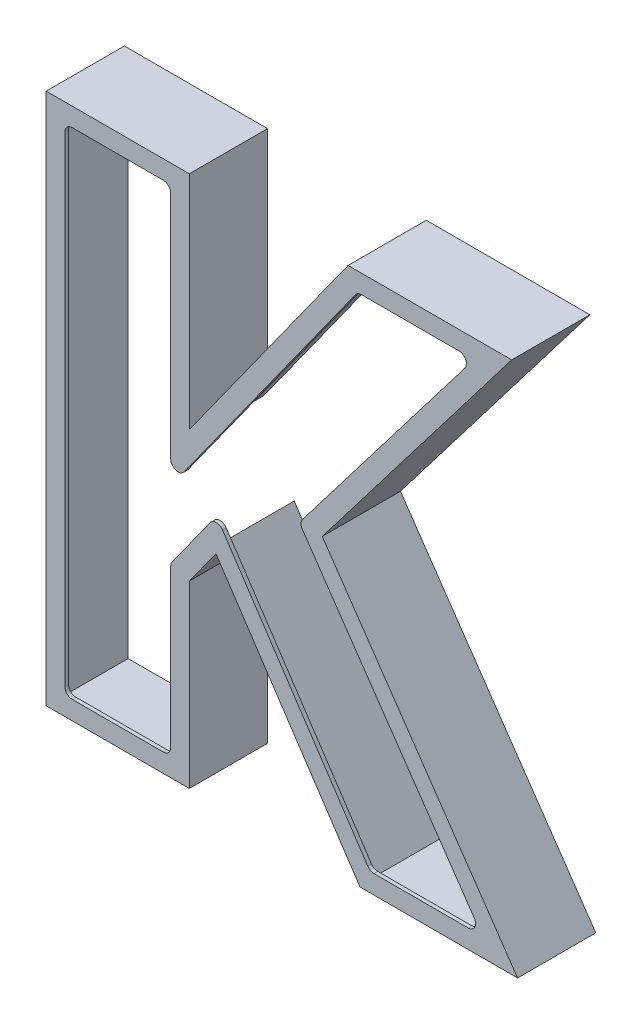
SolidWorks part; units mm, degrees
ref_plane "Front Plane" through (0, 0, 0) normal (0, 0, 1) x (1, 0, 0)
ref_plane "Top Plane" through (0, 0, 0) normal (0, 1, 0) x (1, 0, 0)
ref_plane "Right Plane" through (0, 0, 0) normal (1, 0, 0) x (0, 0, -1)
sketch "Sketch1" plane through (0, 0, 0) normal (0, 0, 1) x (1, 0, 0)
  line L90 (3103.5775, -1502.5826) -> (3065.1345, -1502.5826)
  line L91 (3103.5775, -1562.1032) -> (3103.5775, -1502.5826)
  line L92 (3146.2199, -1502.5826) -> (3103.5775, -1562.1032)
  line L93 (3190.1772, -1502.5826) -> (3146.2199, -1502.5826)
  line L94 (3139.2895, -1569.0911) -> (3190.1772, -1502.5826)
  line L95 (3191.7609, -1645.5826) -> (3139.2895, -1569.0911)
  line L96 (3149.4263, -1645.5826) -> (3191.7609, -1645.5826)
  line L97 (3110.7244, -1587.3803) -> (3149.4263, -1645.5826)
  line L98 (3103.5775, -1597.3267) -> (3110.7244, -1587.3803)
  line L99 (3103.5775, -1645.5826) -> (3103.5775, -1597.3267)
  line L100 (3065.1345, -1502.5826) -> (3065.1345, -1645.5826)
  line L101 (3065.1345, -1645.5826) -> (3103.5775, -1645.5826)
  line L102 (3103.5775, -1502.5826) -> (3065.1345, -1502.5826)
  line L103 (3103.5775, -1562.1032) -> (3103.5775, -1502.5826)
  line L104 (3146.2199, -1502.5826) -> (3103.5775, -1562.1032)
  line L105 (3190.1772, -1502.5826) -> (3146.2199, -1502.5826)
  line L106 (3139.2895, -1569.0911) -> (3190.1772, -1502.5826)
  line L107 (3191.7609, -1645.5826) -> (3139.2895, -1569.0911)
  line L108 (3149.4263, -1645.5826) -> (3191.7609, -1645.5826)
  line L109 (3110.7244, -1587.3803) -> (3149.4263, -1645.5826)
  line L110 (3103.5775, -1597.3267) -> (3110.7244, -1587.3803)
  line L111 (3103.5775, -1645.5826) -> (3103.5775, -1597.3267)
  line L112 (3065.1345, -1502.5826) -> (3065.1345, -1645.5826)
  line L113 (3065.1345, -1645.5826) -> (3103.5775, -1645.5826)
  dimension "D1" = 1.5
extrude "Boss-Extrude1" add sketch "Sketch1" along normal blind 1 and the other way blind 20
sketch "Sketch2" plane through (0, 0, 1) normal (0, 0, 1) x (1, 0, 0)
  line L24 (3098.5775, -1577.6675) -> (3098.5775, -1507.5826)
  line L25 (3098.5775, -1507.5826) -> (3070.1345, -1507.5826)
  line L26 (3070.1345, -1507.5826) -> (3070.1345, -1640.5826)
  line L27 (3070.1345, -1640.5826) -> (3098.5775, -1640.5826)
  line L28 (3098.5775, -1640.5826) -> (3098.5775, -1595.7166)
  line L29 (3098.5775, -1595.7166) -> (3110.8837, -1578.5899)
  line L30 (3110.8837, -1578.5899) -> (3152.106, -1640.5826)
  line L31 (3152.106, -1640.5826) -> (3182.2677, -1640.5826)
  line L32 (3182.2677, -1640.5826) -> (3133.1163, -1568.9309)
  line L33 (3133.1163, -1568.9309) -> (3180.0559, -1507.5826)
  line L34 (3180.0559, -1507.5826) -> (3148.7885, -1507.5826)
  line L35 (3148.7885, -1507.5826) -> (3098.5775, -1577.6675)
  line L36 (3098.5775, -1577.6675) -> (3098.5775, -1507.5826)
  line L37 (3098.5775, -1507.5826) -> (3070.1345, -1507.5826)
  line L38 (3070.1345, -1507.5826) -> (3070.1345, -1640.5826)
  line L39 (3070.1345, -1640.5826) -> (3098.5775, -1640.5826)
  line L40 (3098.5775, -1640.5826) -> (3098.5775, -1595.7166)
  line L41 (3098.5775, -1595.7166) -> (3110.8837, -1578.5899)
  line L42 (3110.8837, -1578.5899) -> (3152.106, -1640.5826)
  line L43 (3152.106, -1640.5826) -> (3182.2677, -1640.5826)
  line L44 (3182.2677, -1640.5826) -> (3133.1163, -1568.9309)
  line L45 (3133.1163, -1568.9309) -> (3180.0559, -1507.5826)
  line L46 (3180.0559, -1507.5826) -> (3148.7885, -1507.5826)
  line L47 (3148.7885, -1507.5826) -> (3098.5775, -1577.6675)
  dimension "D1" = 5
extrude "Cut-Extrude1" cut sketch "Sketch2" against normal through all
sketch "Sketch3" plane through (0, 0, -20) normal (0, 0, -1) x (-1, 0, 0)
  line L24 (-3102.5775, -1503.5826) -> (-3102.5775, -1565.216)
  line L25 (-3102.5775, -1565.216) -> (-3146.7336, -1503.5826)
  line L26 (-3146.7336, -1503.5826) -> (-3188.153, -1503.5826)
  line L27 (-3188.153, -1503.5826) -> (-3138.0548, -1569.059)
  line L28 (-3138.0548, -1569.059) -> (-3189.8623, -1644.5826)
  line L29 (-3189.8623, -1644.5826) -> (-3149.9622, -1644.5826)
  line L30 (-3149.9622, -1644.5826) -> (-3110.7562, -1585.6222)
  line L31 (-3110.7562, -1585.6222) -> (-3102.5775, -1597.0047)
  line L32 (-3102.5775, -1597.0047) -> (-3102.5775, -1644.5826)
  line L33 (-3102.5775, -1644.5826) -> (-3066.1345, -1644.5826)
  line L34 (-3066.1345, -1644.5826) -> (-3066.1345, -1503.5826)
  line L35 (-3066.1345, -1503.5826) -> (-3102.5775, -1503.5826)
  line L36 (-3102.5775, -1503.5826) -> (-3102.5775, -1565.216)
  line L37 (-3102.5775, -1565.216) -> (-3146.7336, -1503.5826)
  line L38 (-3146.7336, -1503.5826) -> (-3188.153, -1503.5826)
  line L39 (-3188.153, -1503.5826) -> (-3138.0548, -1569.059)
  line L40 (-3138.0548, -1569.059) -> (-3189.8623, -1644.5826)
  line L41 (-3189.8623, -1644.5826) -> (-3149.9622, -1644.5826)
  line L42 (-3149.9622, -1644.5826) -> (-3110.7562, -1585.6222)
  line L43 (-3110.7562, -1585.6222) -> (-3102.5775, -1597.0047)
  line L44 (-3102.5775, -1597.0047) -> (-3102.5775, -1644.5826)
  line L45 (-3102.5775, -1644.5826) -> (-3066.1345, -1644.5826)
  line L46 (-3066.1345, -1644.5826) -> (-3066.1345, -1503.5826)
  line L47 (-3066.1345, -1503.5826) -> (-3102.5775, -1503.5826)
  dimension "D1" = 1
extrude "Cut-Extrude2" cut sketch "Sketch3" against normal blind 20
fillet "Fillet1" radius 2 12 edges at (3070.1345, -1507.5826, 0.5) (3098.5775, -1507.5826, 0.5) (3148.7885, -1507.5826, 0.5) (3180.0559, -1507.5826, 0.5) (3133.1163, -1568.9309, 0.5) (3182.2677, -1640.5826, 0.5) (3152.106, -1640.5826, 0.5) (3098.5775, -1577.6675, 0.5) (3110.8837, -1578.5899, 0.5) (3098.5775, -1595.7166, 0.5) (3098.5775, -1640.5826, 0.5) (3070.1345, -1640.5826, 0.5)
